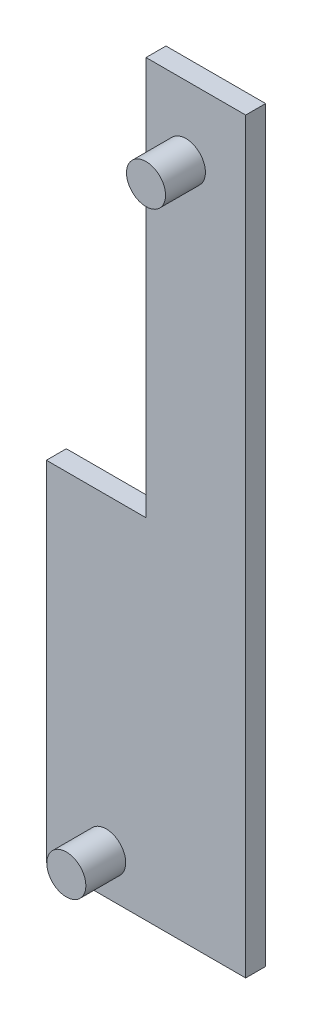
SolidWorks part; units mm, degrees
ref_plane "Front Plane" through (0, 0, 0) normal (0, 0, 1) x (1, 0, 0)
ref_plane "Top Plane" through (0, 0, 0) normal (0, 1, 0) x (1, 0, 0)
ref_plane "Right Plane" through (0, 0, 0) normal (1, 0, 0) x (0, 0, -1)
sketch "Sketch1" plane through (0, 0, 0) normal (0, 0, 1) x (1, 0, 0)
  line L1 (0, 0) -> (50, 0)
  line L2 (0, 0) -> (0, 187.5)
  line L3 (0, 187.5) -> (50, 187.5)
  line L4 (50, 0) -> (50, 187.5)
  dimension "D1" = 50
  dimension "D2" = 187.5
extrude "Boss-Extrude1" add sketch "Sketch1" along normal blind 5
sketch "Sketch2" plane through (0, 0, 5) normal (0, 0, 1) x (1, 0, 0)
  line L0 (0, 0) -> (50, 0) construction
  line L1 (0, 187.5) -> (0, 0) construction
  line L2 (50, 187.5) -> (0, 187.5) construction
  circle A0 centre (15, 10) radius 4.9
  circle A1 centre (35, 170) radius 4.9
  dimension "D1" = 9.8
  dimension "D2" = 10
  dimension "D3" = 15
  dimension "D4" = 17.5
  dimension "D5" = 9.8
  dimension "D6" = 20
extrude "Boss-Extrude2" add sketch "Sketch2" along normal blind 10
sketch "Sketch3" plane through (0, 0, 5) normal (0, 0, 1) x (1, 0, 0)
  line L1 (0, 187.5) -> (25, 187.5)
  line L2 (0, 187.5) -> (0, 87.5)
  line L3 (0, 87.5) -> (25, 87.5)
  line L4 (25, 187.5) -> (25, 87.5)
  dimension "D1" = 25
  dimension "D2" = 100
extrude "Cut-Extrude1" cut sketch "Sketch3" against normal blind 10
